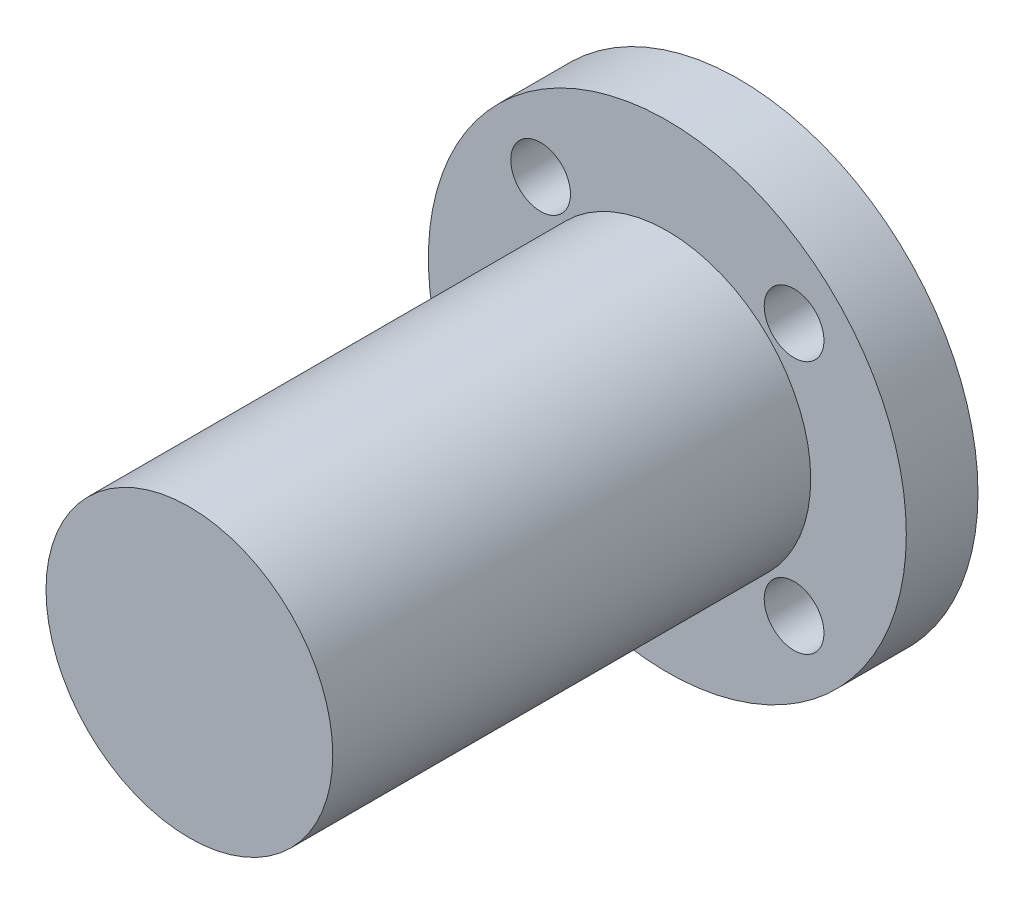
SolidWorks part; units mm, degrees
ref_plane "前视基准面" through (0, 0, 0) normal (0, 0, 1) x (1, 0, 0)
ref_plane "上视基准面" through (0, 0, 0) normal (0, 1, 0) x (1, 0, 0)
ref_plane "右视基准面" through (0, 0, 0) normal (1, 0, 0) x (0, 0, -1)
sketch "草图1" plane through (0, 0, 0) normal (0, 0, 1) x (1, 0, 0)
  circle A0 centre (0, 0) radius 10
  dimension "D1" = 20
extrude "凸台-拉伸1" add sketch "草图1" along normal blind 3
sketch "草图2" plane through (0, 0, 3) normal (0, 0, 1) x (1, 0, 0)
  circle A0 centre (0, 0) radius 6
  dimension "D1" = 12
extrude "凸台-拉伸2" add sketch "草图2" along normal blind 20
sketch "草图4" plane through (0, 0, 0) normal (0, 0, -1) x (-1, 0, 0)
  line L1 (5.3033, -5.3033) -> (-5.3033, -5.3033) construction
  line L2 (5.3033, -5.3033) -> (5.3033, 5.3033) construction
  line L3 (5.3033, 5.3033) -> (-5.3033, 5.3033) construction
  line L4 (-5.3033, -5.3033) -> (-5.3033, 5.3033) construction
  line L5 (5.3033, -5.3033) -> (-5.3033, 5.3033) construction
  line L6 (5.3033, 5.3033) -> (-5.3033, -5.3033) construction
  circle A0 centre (-5.3033, 5.3033) radius 1.25
  circle A1 centre (5.3033, 5.3033) radius 1.25
  circle A2 centre (5.3033, -5.3033) radius 1.25
  circle A3 centre (-5.3033, -5.3033) radius 1.25
  point P0 (0, 0)
  dimension "D2" = 2.5
  dimension "D1" = 15
extrude "切除-拉伸1" cut sketch "草图4" against normal up to next
